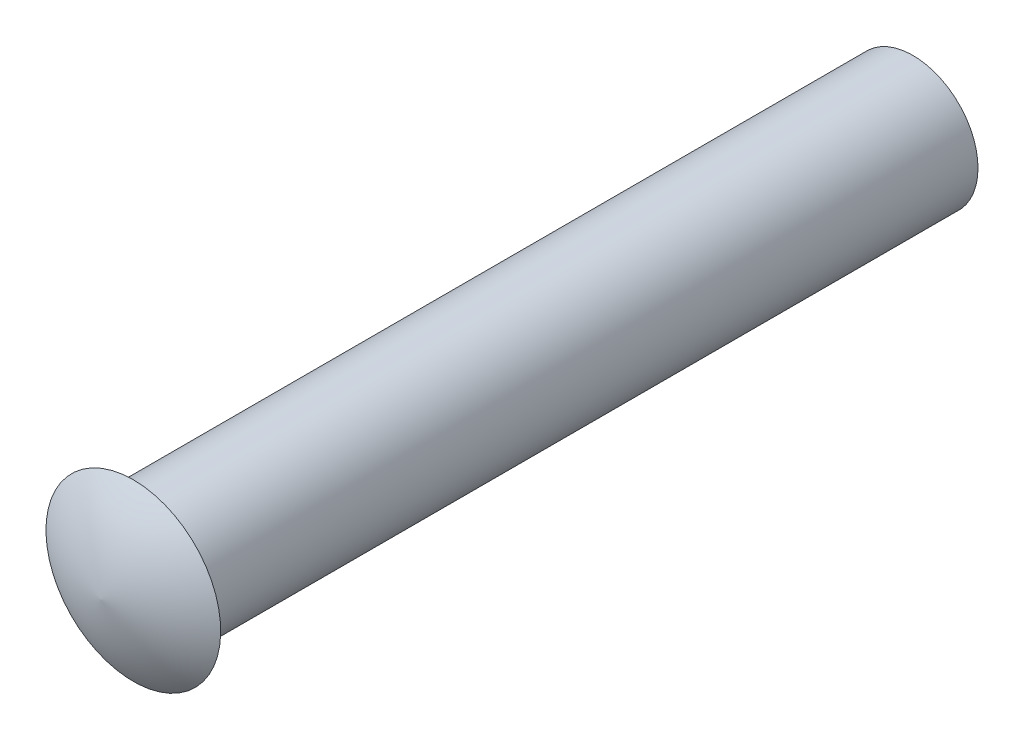
SolidWorks part; units mm, degrees
material "Alloy Steel"
ref_plane "Front Plane" through (0, 0, 0) normal (0, 0, 1) x (1, 0, 0)
ref_plane "Top Plane" through (0, 0, 0) normal (0, 1, 0) x (1, 0, 0)
ref_plane "Right Plane" through (0, 0, 0) normal (1, 0, 0) x (0, 0, -1)
sketch "Sketch2" plane through (0, 0, 0) normal (0, 0, 1) x (1, 0, 0)
  circle A0 centre (0, 0) radius 1.59
extrude "Boss-Extrude1" add sketch "Sketch2" against normal blind 19.05
sketch3d "3DSketch1"
  circle A0 centre (0, 0, 0) radius 2.135
  point P2 (0, 0, 2.135)
sketch "Sketch5" plane through (0, 0, 0) normal (1, 0, 0) x (0, 0, -1)
  line L0 (0, 0) -> (-0.79, 0)
  line L1 (0, 0) -> (0, 2.135)
  line L2 (0, 2.135) -> (0, -2.135) construction
  arc A0 (-0.79, 0) -> (0, 2.135) centre (3.6836, -0.4417) cw
  dimension "D1" = 0.79
revolve "Revolve1" add sketch "Sketch5" angle 360 about L0
